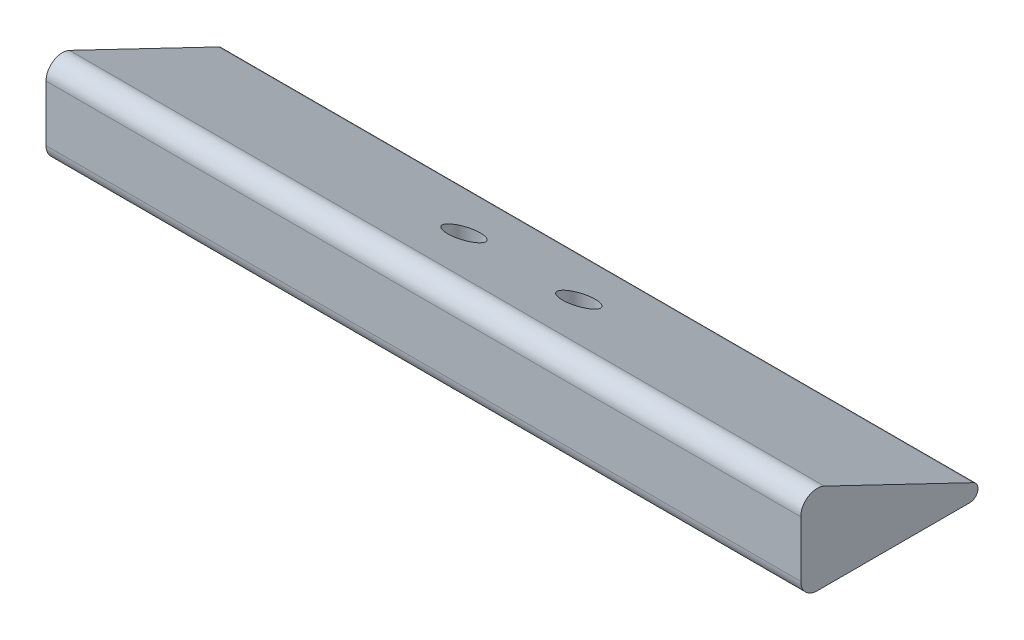
SolidWorks part; units mm, degrees
material "Rubber"
ref_plane "Front Plane" through (0, 0, 0) normal (0, 0, 1) x (1, 0, 0)
ref_plane "Top Plane" through (0, 0, 0) normal (0, 1, 0) x (1, 0, 0)
ref_plane "Right Plane" through (0, 0, 0) normal (1, 0, 0) x (0, 0, -1)
sketch "Sketch1" plane through (0, 0, 0) normal (1, 0, 0) x (0, 0, -1)
  line L0 (2, 0) -> (20.6058, 0)
  line L1 (21.0385, 1.9015) -> (2.8655, 10.6246)
  line L2 (0, 8.8215) -> (0, 2)
  arc A0 (0, 8.8215) -> (2.8655, 10.6246) centre (2, 8.8215) cw
  arc A1 (2, 0) -> (0, 2) centre (2, 2) cw
  arc A2 (21.0385, 1.9015) -> (20.6058, 0) centre (20.6058, 1) cw
  point P6 (0, 12)
  point P9 (0, 0)
  point P12 (25, 0)
  dimension "D1" = 12
  dimension "D3" = 2
  dimension "D4" = 1
  dimension "D2" = 25
extrude "Boss-Extrude1" add sketch "Sketch1" along normal blind 92
ref_plane "Plane1" through (0, 10, 0) normal (0, 1, 0) x (1, 0, 0)
sketch "Sketch2" plane through (0, 10, 0) normal (0, 1, 0) x (1, 0, 0)
  line L0 (92, 11.952) -> (0, 11.952) construction
  line L1 (92, 21.0385) -> (92, 2.8655) construction
  line L2 (0, 21.0385) -> (0, 2.8655) construction
  line L3 (46, 11.952) -> (46, 18.9766) construction
  line L4 (46, 11.952) -> (46, 18.9766) construction
  circle A0 centre (39, 11.952) radius 2
  circle A2 centre (53, 11.952) radius 2
  dimension "D1" = 4
  dimension "D2" = 7
  dimension "D3" = 0
extrude "Cut-Extrude1" cut sketch "Sketch2" against normal blind 8
sketch "Sketch3" plane through (0, 2, 0) normal (0, 1, 0) x (1, 0, 0)
  circle A0 centre (39, 11.952) radius 1.5
  circle A1 centre (53, 11.952) radius 1.5
  circle A2 centre (53, 11.952) radius 2 construction
  dimension "D1" = 3
extrude "Cut-Extrude2" cut sketch "Sketch3" against normal through all
sketch "Sketch4" [suppressed] plane through (0, 0, 0) normal (1, 0, 0) x (0, 0, -1)
  line L0 (0, 1) -> (0, 10.4108)
  line L1 (1.4327, 11.3123) -> (21.0385, 1.9015)
  line L2 (20.6058, 0) -> (1, 0)
  arc A0 (20.6058, 0) -> (21.0385, 1.9015) centre (20.6058, 1) ccw
  arc A1 (1, 0) -> (0, 1) centre (1, 1) cw
  arc A2 (1.4327, 11.3123) -> (0, 10.4108) centre (1, 10.4108) ccw
  point P6 (25, 0)
  point P9 (0, 0)
  point P12 (0, 12)
  dimension "D3" = 1
  dimension "D1" = 25
  dimension "D2" = 12
extrude "Boss-Extrude2" [suppressed] add sketch "Sketch4" along normal blind 40
ref_plane "Plane2" [suppressed] through (0, 10, 0) normal (0, -1, 0) x (-1, 0, 0)
sketch "Sketch5" [suppressed] plane through (0, 10, 0) normal (0, -1, 0) x (-1, 0, 0)
  line L0 (-15, 0) -> (-15, 21.6058) construction
  line L1 (-30, 0) -> (0, 0) construction
  line L2 (0, 21.6058) -> (-30, 21.6058) construction
  line L3 (-15, 10.8029) -> (-8, 10.8029) construction
  circle A0 centre (-8, 10.8029) radius 2
  circle A1 centre (-22, 10.8029) radius 2
  dimension "D1" = 4
  dimension "D2" = 14
extrude "Cut-Extrude4" [suppressed] cut sketch "Sketch5" along normal blind 8
sketch "Sketch6" [suppressed] plane through (0, 2, 0) normal (0, 1, 0) x (1, 0, 0)
  circle A0 centre (8, 10.8029) radius 1.5
  circle A1 centre (22, 10.8029) radius 1.5
  dimension "D1" = 3
extrude "Cut-Extrude5" [suppressed] cut sketch "Sketch6" against normal blind 8
